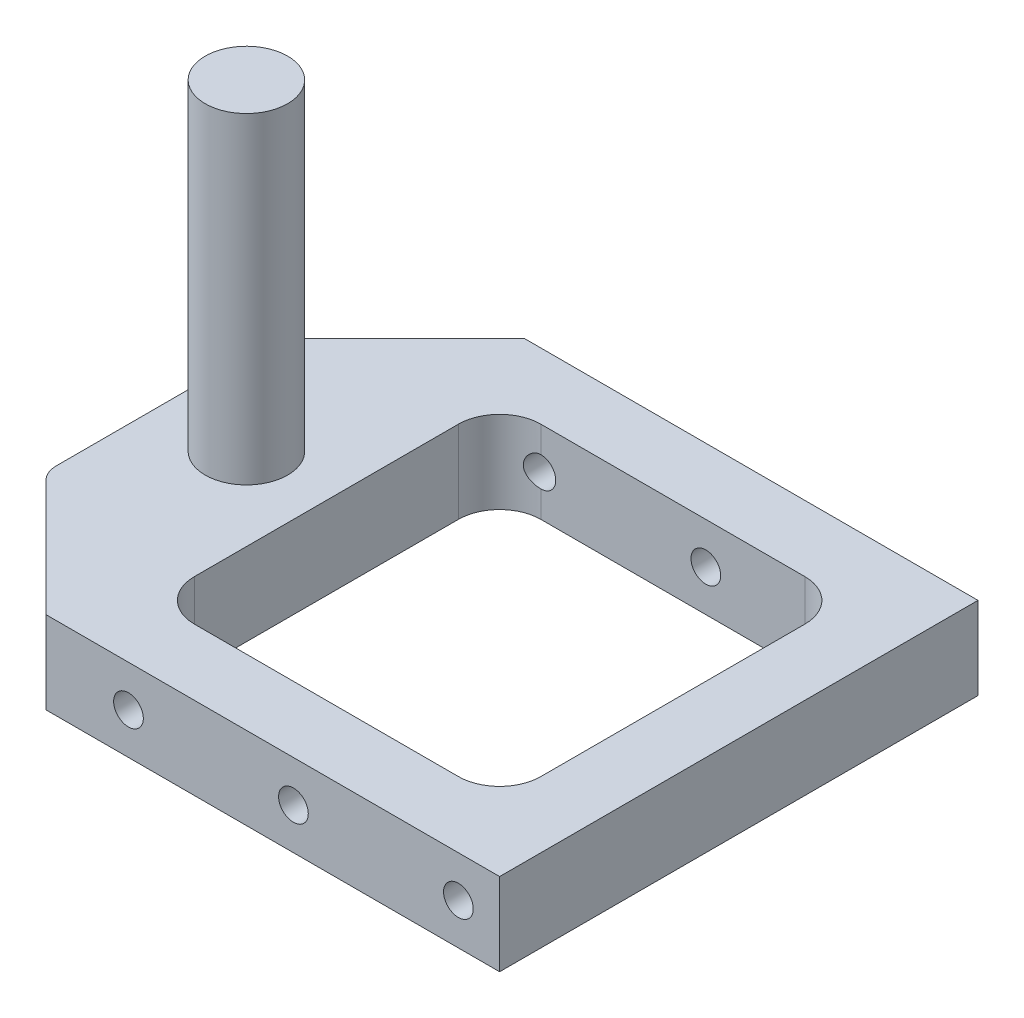
SolidWorks part; units mm, degrees
material "AISI 304"
ref_plane "Front Plane" through (0, 0, 0) normal (0, 0, 1) x (1, 0, 0)
ref_plane "Top Plane" through (0, 0, 0) normal (0, 1, 0) x (1, 0, 0)
ref_plane "Right Plane" through (0, 0, 0) normal (1, 0, 0) x (0, 0, -1)
sketch "Sketch1" plane through (0, 0, 0) normal (0, 0, 1) x (1, 0, 0)
  line L1 (24.9678, -105) -> (-45.0322, -105)
  line L2 (24.9678, -105) -> (24.9678, -95)
  line L3 (24.9678, -95) -> (-45.0322, -95)
  line L4 (-45.0322, -105) -> (-45.0322, -95)
  dimension "D1" = 10
  dimension "D2" = 70
extrude "Extrude1" add sketch "Sketch1" along normal blind 58
sketch "Sketch2" plane through (0, -105, 0) normal (0, -1, 0) x (1, 0, 0)
  line L0 (27.6368, 43.7) -> (27.6368, 13.7) construction
  line L1 (38.7, 43.7) -> (-38.7, 43.7) construction
  line L2 (-38.7, 13.7) -> (38.7, 13.7) construction
  line L3 (27.6368, 28.7) -> (-35.0322, 28.7) construction
  line L4 (-45.0322, 58) -> (-45.0322, 0) construction
  circle A0 centre (-35.0322, 28.7) radius 5
  dimension "D2" = 10
  dimension "D1" = 10
extrude "Extrude2" add sketch "Sketch2" against normal blind 49
sketch "Sketch3" plane through (0, -105, 0) normal (0, -1, 0) x (1, 0, 0)
  line L0 (-45.0322, 58) -> (24.9678, 58) construction
  line L1 (-20.0322, 50) -> (11.9678, 50)
  line L2 (-25.0322, 45) -> (-25.0322, 13)
  line L3 (-20.0322, 8) -> (11.9678, 8)
  line L4 (16.9678, 45) -> (16.9678, 13)
  line L5 (-45.0322, 0) -> (24.9678, 0) construction
  line L6 (24.9678, 58) -> (24.9678, 0) construction
  line L7 (-45.0322, 58) -> (-45.0322, 0) construction
  arc A0 (-25.0322, 13) -> (-20.0322, 8) centre (-20.0322, 13) ccw
  arc A1 (11.9678, 8) -> (16.9678, 13) centre (11.9678, 13) ccw
  arc A2 (11.9678, 50) -> (16.9678, 45) centre (11.9678, 45) cw
  arc A3 (-20.0322, 50) -> (-25.0322, 45) centre (-20.0322, 45) ccw
  dimension "D5" = 5
  dimension "D1" = 8
  dimension "D2" = 8
  dimension "D3" = 8
  dimension "D4" = 20
extrude "Cut-Extrude1" cut sketch "Sketch3" against normal blind 30
chamfer "Chamfer1" distance 15 angle 45 2 edges at (-45.0322, -100, 0) (-45.0322, -100, 58)
fillet "Fillet1" radius 3 2 edges at (-45.0322, -100, 15) (-45.0322, -100, 43)
sketch "Sketch4" plane through (0, 0, 58) normal (0, 0, 1) x (1, 0, 0)
  circle A0 centre (-20.0322, -100) radius 1.8
  circle A1 centre (-0.0322, -100) radius 1.8
  circle A2 centre (19.9678, -100) radius 1.8
  dimension "D1" = 3.6
extrude "Cut-Extrude2" cut sketch "Sketch4" against normal blind 60
